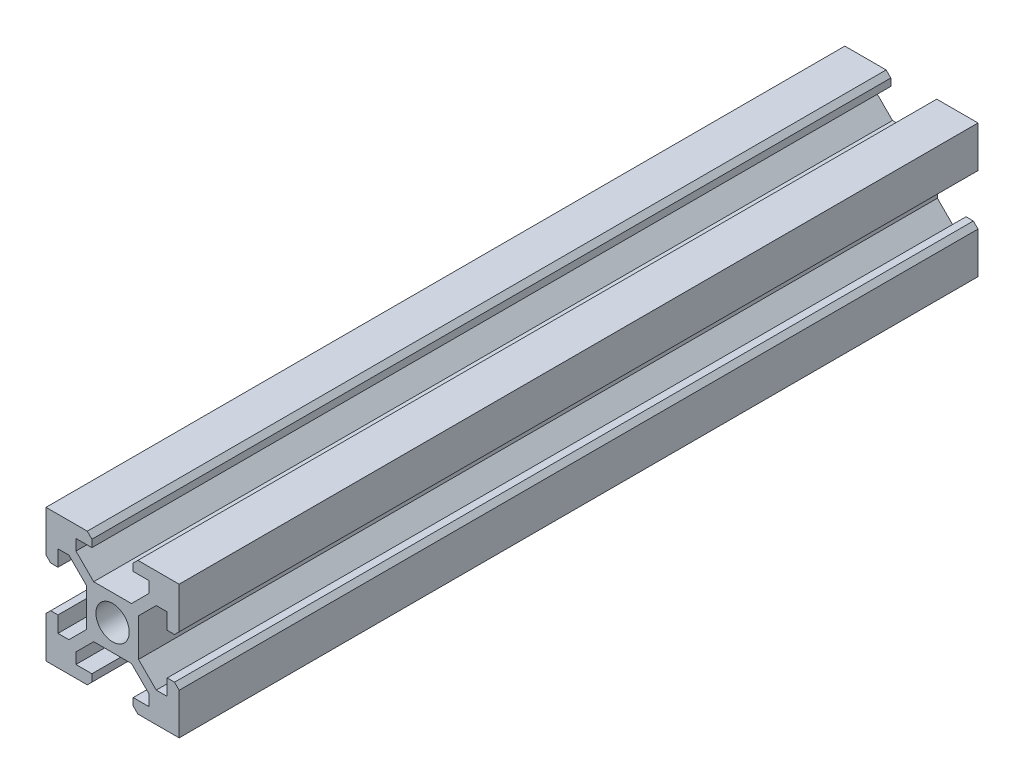
SolidWorks part; units mm, degrees
material "1060 Alloy"
ref_plane "Front Plane" through (0, 0, 0) normal (0, 0, 1) x (1, 0, 0)
ref_plane "Top Plane" through (0, 0, 0) normal (0, 1, 0) x (1, 0, 0)
ref_plane "Right Plane" through (0, 0, 0) normal (1, 0, 0) x (0, 0, -1)
sketch "Sketch1" plane through (0, 0, 0) normal (0, 0, 1) x (1, 0, 0)
  line L0 (3.9, -2.8393) -> (6.5607, -5.5)
  line L1 (-10, 10) -> (10, 10) construction
  line L2 (-10, 10) -> (-10, -10) construction
  line L3 (-10, -10) -> (10, -10) construction
  line L4 (10, 10) -> (10, -10) construction
  line L5 (-10, 10) -> (10, -10) construction
  line L6 (-10, -10) -> (10, 10) construction
  line L7 (-3.9, -3.9) -> (3.9, -3.9) construction
  line L8 (-3.9, -3.9) -> (-3.9, 3.9) construction
  line L9 (-3.9, 3.9) -> (3.9, 3.9) construction
  line L10 (3.9, -3.9) -> (3.9, 3.9) construction
  line L11 (-3.9, -3.9) -> (3.9, 3.9) construction
  line L12 (-3.9, 3.9) -> (3.9, -3.9) construction
  line L13 (-10, 10) -> (-5.5, 10) construction
  line L14 (-10, 10) -> (-10, 5.5) construction
  line L15 (-10, 5.5) -> (-5.5, 5.5) construction
  line L16 (-5.5, 10) -> (-5.5, 5.5) construction
  line L17 (10, 10) -> (5.5, 10) construction
  line L18 (10, 10) -> (10, 5.5) construction
  line L19 (10, 5.5) -> (5.5, 5.5) construction
  line L20 (5.5, 10) -> (5.5, 5.5) construction
  line L21 (-10, -10) -> (-5.5, -10) construction
  line L22 (-10, -10) -> (-10, -5.5) construction
  line L23 (-10, -5.5) -> (-5.5, -5.5) construction
  line L24 (-5.5, -10) -> (-5.5, -5.5) construction
  line L25 (10, -10) -> (5.5, -10) construction
  line L26 (10, -10) -> (10, -5.5) construction
  line L27 (10, -5.5) -> (5.5, -5.5) construction
  line L28 (5.5, -10) -> (5.5, -5.5) construction
  line L29 (2.8393, -3.9) -> (5.5, -6.5607)
  line L30 (-5.5, 6.5607) -> (-2.8393, 3.9)
  line L31 (-6.5607, 5.5) -> (-3.9, 2.8393)
  line L32 (5.5, 6.5607) -> (2.8393, 3.9)
  line L33 (6.5607, 5.5) -> (3.9, 2.8393)
  line L34 (-6.5607, -5.5) -> (-3.9, -2.8393)
  line L35 (-5.5, -6.5607) -> (-2.8393, -3.9)
  line L36 (-2.8393, 3.9) -> (2.8393, 3.9)
  line L37 (-3.9, 2.8393) -> (-3.9, -2.8393)
  line L38 (-2.8393, -3.9) -> (2.8393, -3.9)
  line L39 (3.9, -2.8393) -> (3.9, 2.8393)
  line L40 (5.5, 6.5607) -> (5.5, 8.2007)
  line L41 (5.5, 8.2007) -> (3.1, 8.2007)
  line L42 (3.1, 8.2007) -> (3.1, 9.3)
  line L43 (3.1, 9.3) -> (3.8, 10)
  line L44 (3.8, 10) -> (10, 10)
  line L45 (10, 10) -> (10, 3.8)
  line L46 (10, 3.8) -> (9.3, 3.1)
  line L47 (9.3, 3.1) -> (8.2007, 3.1)
  line L48 (8.2007, 3.1) -> (8.2007, 5.5)
  line L49 (8.2007, 5.5) -> (6.5607, 5.5)
  line L50 (3.1, -8.2007) -> (5.5, -8.2007)
  line L51 (3.1, -9.3) -> (3.1, -8.2007)
  line L52 (3.8, -10) -> (3.1, -9.3)
  line L53 (10, -10) -> (3.8, -10)
  line L54 (10, -3.8) -> (10, -10)
  line L55 (9.3, -3.1) -> (10, -3.8)
  line L56 (8.2007, -3.1) -> (9.3, -3.1)
  line L57 (8.2007, -5.5) -> (8.2007, -3.1)
  line L58 (6.5607, -5.5) -> (8.2007, -5.5)
  line L59 (5.5, -8.2007) -> (5.5, -6.5607)
  line L60 (-8.2007, -3.1) -> (-8.2007, -5.5)
  line L61 (-9.3, -3.1) -> (-8.2007, -3.1)
  line L62 (-10, -3.8) -> (-9.3, -3.1)
  line L63 (-10, -10) -> (-10, -3.8)
  line L64 (-3.8, -10) -> (-10, -10)
  line L65 (-3.1, -9.3) -> (-3.8, -10)
  line L66 (-3.1, -8.2007) -> (-3.1, -9.3)
  line L67 (-5.5, -8.2007) -> (-3.1, -8.2007)
  line L68 (-5.5, -6.5607) -> (-5.5, -8.2007)
  line L69 (-8.2007, -5.5) -> (-6.5607, -5.5)
  line L70 (-3.1, 8.2007) -> (-5.5, 8.2007)
  line L71 (-3.1, 9.3) -> (-3.1, 8.2007)
  line L72 (-3.8, 10) -> (-3.1, 9.3)
  line L73 (-10, 10) -> (-3.8, 10)
  line L74 (-10, 3.8) -> (-10, 10)
  line L75 (-9.3, 3.1) -> (-10, 3.8)
  line L76 (-8.2007, 3.1) -> (-9.3, 3.1)
  line L77 (-8.2007, 5.5) -> (-8.2007, 3.1)
  line L78 (-6.5607, 5.5) -> (-8.2007, 5.5)
  line L79 (-5.5, 8.2007) -> (-5.5, 6.5607)
  circle A0 centre (0, 0) radius 2.5
  point P83 (0, 0)
  dimension "D1" = 5
  dimension "D2" = 20
  dimension "D3" = 7.8
  dimension "D4" = 4.5
  dimension "D5" = 1.5
  dimension "D6" = 0.75
  dimension "D7" = 1.5
  dimension "D8" = 0.75
  dimension "D9" = 1.5
  dimension "D10" = 0.75
  dimension "D11" = 1.5
  dimension "D12" = 0.75
  dimension "D13" = 1.64
  dimension "D14" = 45
  dimension "D15" = 3.1
  dimension "D16" = 6.2
  dimension "D17" = 6.2
  dimension "D18" = 3.1
  dimension "D19" = 4
extrude "Boss-Extrude1" add sketch "Sketch1" along normal mid plane 120 contours L79 L70 L71 L72 L73 L74 L75 L76 L77 L78 L31 L37 L34 L69 L60 L61 L62 L63 L64 L65 L66 L67 L68 L35 L38 L29 L59 L50 L51 L52 L53 L54 L55 L56 L57 L58 L0 L39 L33 L49 L48 L47 L46 L45 L44 L43 L42 L41 L40 L32 L36
